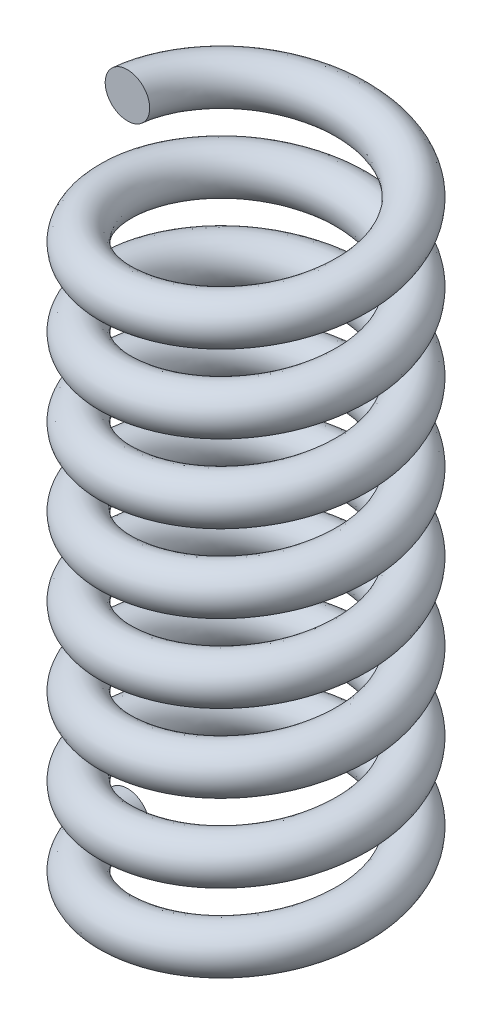
SolidWorks part; units mm, degrees
ref_plane "Front Plane" through (0, 0, 0) normal (0, 0, 1) x (1, 0, 0)
ref_plane "Top Plane" through (0, 0, 0) normal (0, 1, 0) x (1, 0, 0)
ref_plane "Right Plane" through (0, 0, 0) normal (1, 0, 0) x (0, 0, -1)
sketch "Sketch2" plane through (0, 0, 0) normal (0, 1, 0) x (1, 0, 0)
  circle A0 centre (0, 0) radius 4
  dimension "D1" = 8
curve "Helix/Spiral1" pitch 2.625 height 21 turns 8
sketch "Sketch3" plane through (0, 0, 0) normal (0, 0, 1) x (1, 0, 0)
  circle A0 centre (-4, 0) radius 0.75
  spline S0 degree 3 poles (-4, 0) (-4, 0.0543) (-3.7917, 0.1642) (-2.9021, 0.3281) (-1.5706, 0.4922) (0, 0.6562) (1.5706, 0.8203) (2.9021, 0.9844) (3.7917, 1.1484) (4.1041, 1.3125) (3.7917, 1.4766) (2.9021, 1.6406) (1.5706, 1.8047) (0, 1.9687) (-1.5706, 2.1328) (-2.9021, 2.2969) (-3.7917, 2.4609) (-4.1041, 2.625) (-3.7917, 2.7891) (-2.9021, 2.9531) (-1.5706, 3.1172) (0, 3.2812) (1.5706, 3.4453) (2.9021, 3.6094) (3.7917, 3.7734) (4.1041, 3.9375) (3.7917, 4.1016) (2.9021, 4.2656) (1.5706, 4.4297) (0, 4.5938) (-1.5706, 4.7578) (-2.9021, 4.9219) (-3.7917, 5.0859) (-4.1041, 5.25) (-3.7917, 5.4141) (-2.9021, 5.5781) (-1.5706, 5.7422) (0, 5.9063) (1.5706, 6.0703) (2.9021, 6.2344) (3.7917, 6.3984) (4.1041, 6.5625) (3.7917, 6.7266) (2.9021, 6.8906) (1.5706, 7.0547) (0, 7.2188) (-1.5706, 7.3828) (-2.9021, 7.5469) (-3.7917, 7.7109) (-4.1041, 7.875) (-3.7917, 8.0391) (-2.9021, 8.2031) (-1.5706, 8.3672) (0, 8.5312) (1.5706, 8.6953) (2.9021, 8.8594) (3.7917, 9.0234) (4.1041, 9.1875) (3.7917, 9.3516) (2.9021, 9.5156) (1.5706, 9.6797) (0, 9.8437) (-1.5706, 10.0078) (-2.9021, 10.1719) (-3.7917, 10.3359) (-4.1041, 10.5) (-3.7917, 10.6641) (-2.9021, 10.8281) (-1.5706, 10.9922) (0, 11.1562) (1.5706, 11.3203) (2.9021, 11.4844) (3.7917, 11.6484) (4.1041, 11.8125) (3.7917, 11.9766) (2.9021, 12.1406) (1.5706, 12.3047) (0, 12.4687) (-1.5706, 12.6328) (-2.9021, 12.7969) (-3.7917, 12.9609) (-4.1041, 13.125) (-3.7917, 13.2891) (-2.9021, 13.4531) (-1.5706, 13.6172) (0, 13.7812) (1.5706, 13.9453) (2.9021, 14.1094) (3.7917, 14.2734) (4.1041, 14.4375) (3.7917, 14.6016) (2.9021, 14.7656) (1.5706, 14.9297) (0, 15.0937) (-1.5706, 15.2578) (-2.9021, 15.4219) (-3.7917, 15.5859) (-4.1041, 15.75) (-3.7917, 15.9141) (-2.9021, 16.0781) (-1.5706, 16.2422) (0, 16.4062) (1.5706, 16.5703) (2.9021, 16.7344) (3.7917, 16.8984) (4.1041, 17.0625) (3.7917, 17.2266) (2.9021, 17.3906) (1.5706, 17.5547) (0, 17.7187) (-1.5706, 17.8828) (-2.9021, 18.0469) (-3.7917, 18.2109) (-4.1041, 18.375) (-3.7917, 18.5391) (-2.9021, 18.7031) (-1.5706, 18.8672) (0, 19.0313) (1.5706, 19.1953) (2.9021, 19.3594) (3.7917, 19.5234) (4.1041, 19.6875) (3.7917, 19.8516) (2.9021, 20.0156) (1.5706, 20.1797) (0, 20.3438) (-1.5706, 20.5078) (-2.9021, 20.6719) (-3.7917, 20.8358) (-4, 20.9457) (-4, 21) knots 0 0 0 0 0.007813 0.015625 0.023438 0.03125 0.039063 0.046875 0.054688 0.0625 0.070313 0.078125 0.085938 0.09375 0.101563 0.109375 0.117188 0.125 0.132813 0.140625 0.148438 0.15625 0.164063 0.171875 0.179688 0.1875 0.195313 0.203125 0.210938 0.21875 0.226563 0.234375 0.242188 0.25 0.257813 0.265625 0.273438 0.28125 0.289063 0.296875 0.304688 0.3125 0.320313 0.328125 0.335938 0.34375 0.351563 0.359375 0.367188 0.375 0.382813 0.390625 0.398438 0.40625 0.414063 0.421875 0.429688 0.4375 0.445313 0.453125 0.460938 0.46875 0.476563 0.484375 0.492188 0.5 0.507813 0.515625 0.523438 0.53125 0.539063 0.546875 0.554688 0.5625 0.570313 0.578125 0.585938 0.59375 0.601563 0.609375 0.617188 0.625 0.632813 0.640625 0.648438 0.65625 0.664063 0.671875 0.679688 0.6875 0.695313 0.703125 0.710938 0.71875 0.726563 0.734375 0.742188 0.75 0.757813 0.765625 0.773438 0.78125 0.789063 0.796875 0.804688 0.8125 0.820313 0.828125 0.835938 0.84375 0.851563 0.859375 0.867188 0.875 0.882813 0.890625 0.898438 0.90625 0.914063 0.921875 0.929688 0.9375 0.945313 0.953125 0.960938 0.96875 0.976563 0.984375 0.992188 1 1 1 1 construction
  dimension "D1" = 1.5
sweep "Sweep1" add profiles "Sketch3" path "Helix/Spiral1"
